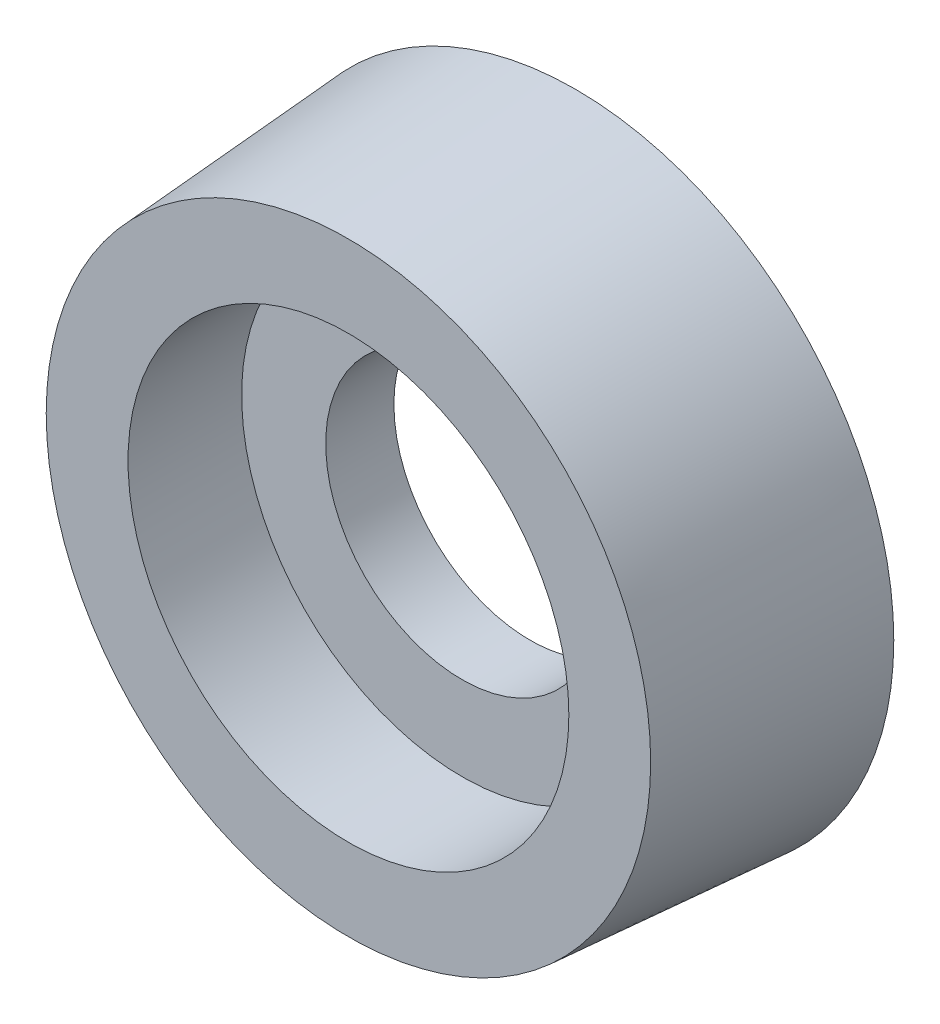
SolidWorks part; units mm, degrees
ref_plane "Спереди" through (0, 0, 0) normal (0, 0, 1) x (1, 0, 0)
ref_plane "Сверху" through (0, 0, 0) normal (0, 1, 0) x (1, 0, 0)
ref_plane "Справа" through (0, 0, 0) normal (1, 0, 0) x (0, 0, -1)
sketch "Эскиз1" plane through (0, 0, 0) normal (0, 0, 1) x (1, 0, 0)
  circle A0 centre (0, 0) radius 7
  dimension "D1" = 14
extrude "Бобышка-Вытянуть1" add sketch "Эскиз1" along normal blind 5 draft 4 contours A0
sketch "Эскиз3" plane through (0, 0, 0) normal (0, 0, -1) x (-1, 0, 0)
  circle A0 centre (0, 0) radius 5
  dimension "D1" = 10
extrude "Вырез-Вытянуть1" cut sketch "Эскиз3" against normal blind 1
sketch "Эскиз4" plane through (0, 0, 5) normal (0, 0, 1) x (1, 0, 0)
  circle A0 centre (0, 0) radius 4.85
  dimension "D1" = 9.7
extrude "Вырез-Вытянуть2" cut sketch "Эскиз4" against normal blind 2.5
sketch "Эскиз5" plane through (0, 0, 2.5) normal (0, 0, 1) x (1, 0, 0)
  circle A0 centre (0, 0) radius 3
  dimension "D1" = 6
extrude "Вырез-Вытянуть3" cut sketch "Эскиз5" against normal through all both and the other way through all
